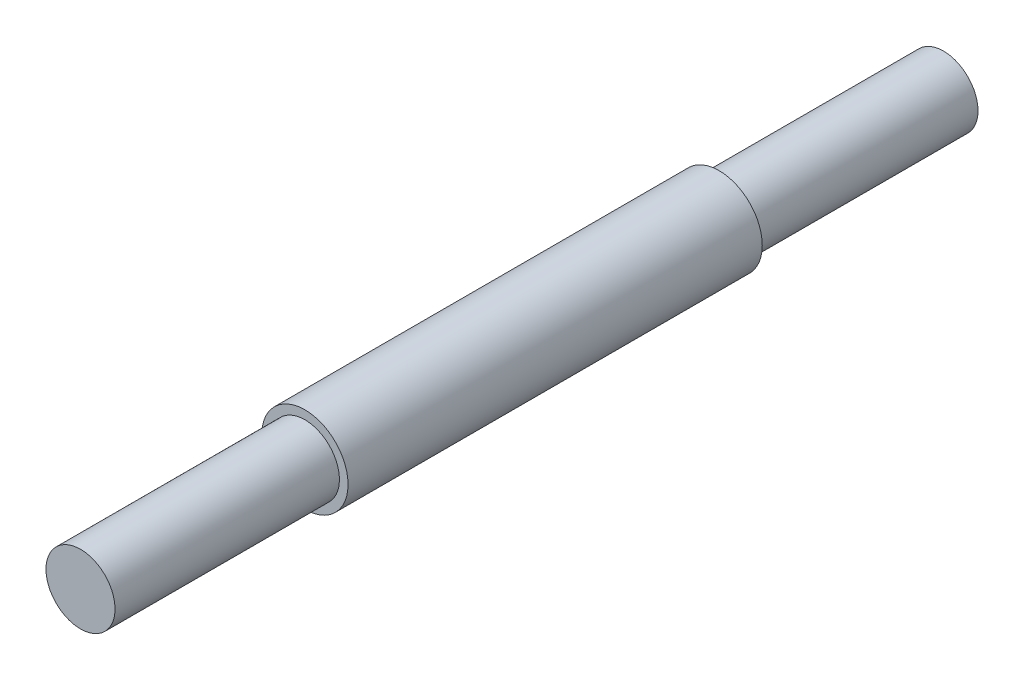
SolidWorks part; units mm, degrees
ref_plane "Plan de face" through (0, 0, 0) normal (0, 0, 1) x (1, 0, 0)
ref_plane "Plan de dessus" through (0, 0, 0) normal (0, 1, 0) x (1, 0, 0)
ref_plane "Plan de droite" through (0, 0, 0) normal (1, 0, 0) x (0, 0, -1)
sketch "Esquisse1" plane through (0, 0, 0) normal (0, 0, 1) x (1, 0, 0)
  circle A0 centre (0, 0) radius 2.5
  dimension "D1" = 5
extrude "Boss.-Extru.1" add sketch "Esquisse1" against normal blind 24
sketch "Esquisse2" plane through (0, 0, 0) normal (0, 0, 1) x (1, 0, 0)
  circle A0 centre (0, 0) radius 2
  dimension "D1" = 4
extrude "Boss.-Extru.2" add sketch "Esquisse2" along normal blind 13
sketch "Esquisse3" plane through (0, 0, -24) normal (0, 0, -1) x (-1, 0, 0)
  circle A0 centre (0, 0) radius 2
  dimension "D1" = 4
extrude "Boss.-Extru.3" add sketch "Esquisse3" along normal blind 13
